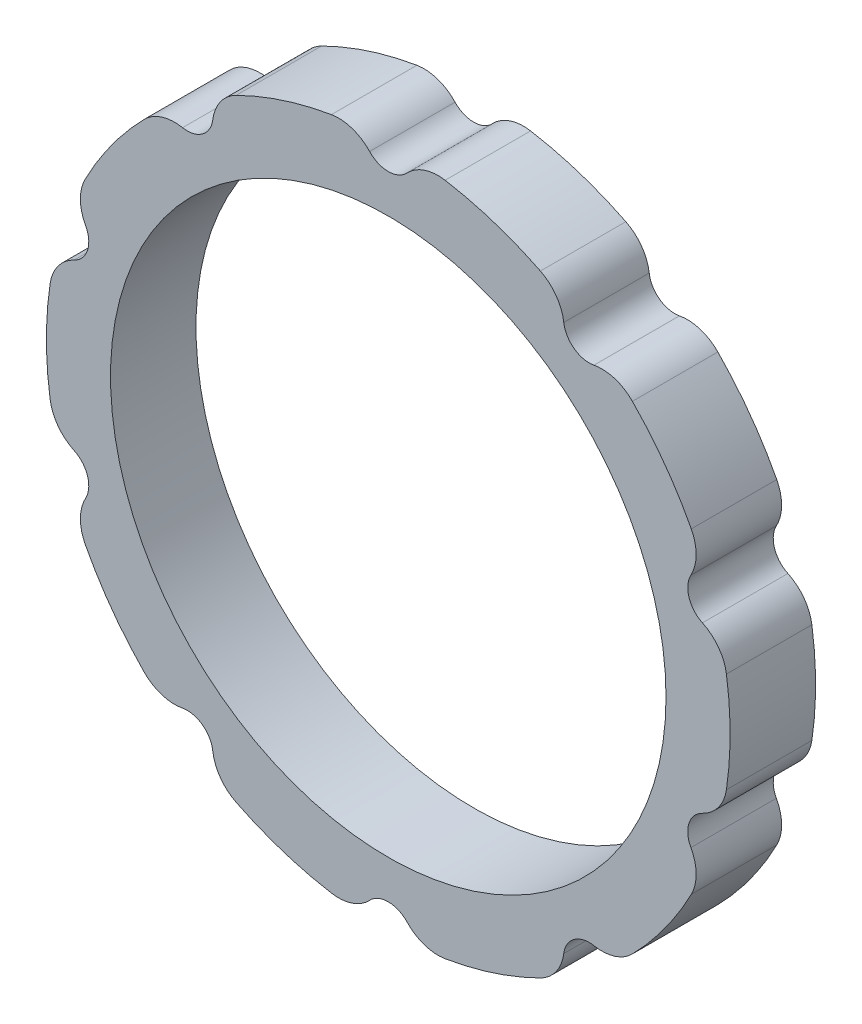
SolidWorks part; units mm, degrees
ref_plane "Front Plane" through (0, 0, 0) normal (0, 0, 1) x (1, 0, 0)
ref_plane "Top Plane" through (0, 0, 0) normal (0, 1, 0) x (1, 0, 0)
ref_plane "Right Plane" through (0, 0, 0) normal (1, 0, 0) x (0, 0, -1)
sketch "Sketch1" plane through (0, 0, 0) normal (0, 0, 1) x (1, 0, 0)
  circle A0 centre (0, 0) radius 16.51
  dimension "D1" = 33.02
extrude "Extrude-Tin1" add sketch "Sketch1" along normal mid plane 5.08 thin
sketch "Sketch2" plane through (0, 0, 2.54) normal (0, 0, 1) x (1, 0, 0)
  circle A0 centre (0, 20.32) radius 1.524
  circle A1 centre (0, 0) radius 20.32 construction
  dimension "D1" = 3.048
extrude "Cut-Extrude1" cut sketch "Sketch2" against normal up to next
fillet "Fillet1" radius 2.54 2 edges at (1.5229, 20.2629, 0) (-1.5229, 20.2629, 0)
pattern_circular "CirPattern1" count 10 over 360 about axis through (0, 0, 0) along (0, 0, 1) of "Fillet1", "Cut-Extrude1"
